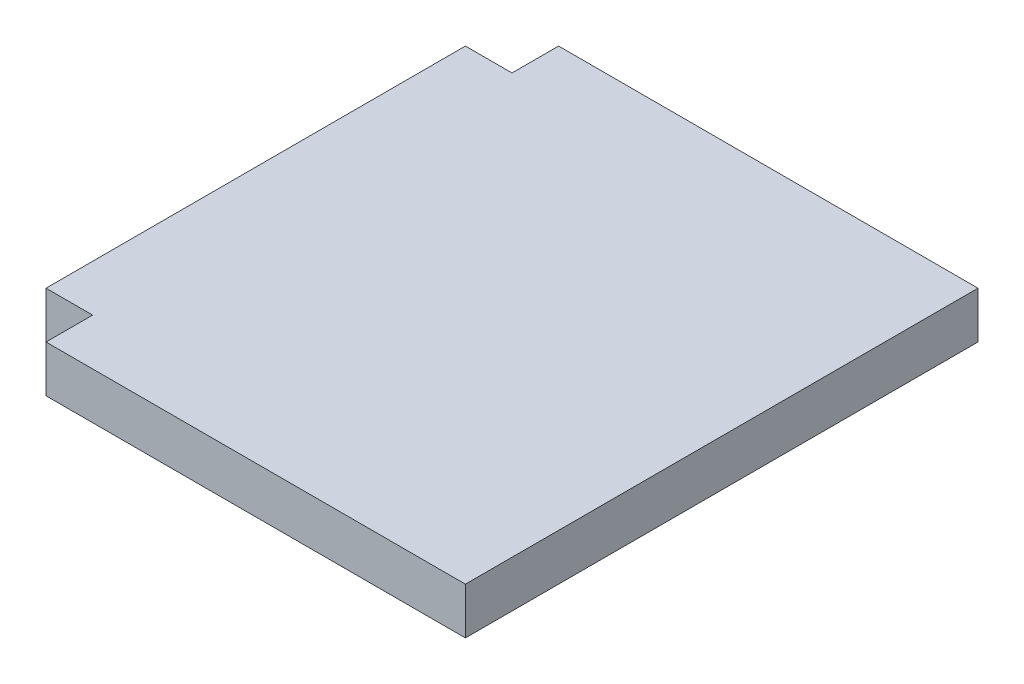
SolidWorks part; units mm, degrees
ref_plane "Alzado" through (0, 0, 0) normal (0, 0, 1) x (1, 0, 0)
ref_plane "Planta" through (0, 0, 0) normal (0, 1, 0) x (1, 0, 0)
ref_plane "Vista lateral" through (0, 0, 0) normal (1, 0, 0) x (0, 0, -1)
sketch "Croquis1" plane through (0, 0, 0) normal (0, 1, 0) x (1, 0, 0)
  line L1 (-250, 275) -> (250, 275)
  line L2 (-250, 275) -> (-250, -275)
  line L3 (-250, -275) -> (250, -275)
  line L4 (250, 275) -> (250, -275)
  line L5 (-250, 275) -> (250, -275) construction
  line L6 (-250, -275) -> (250, 275) construction
  point P0 (0, 0)
  point P7 (0, 0)
  dimension "D1" = 550
  dimension "D2" = 500
extrude "Saliente-Extruir1" add sketch "Croquis1" along normal blind 50
sketch "Croquis2" plane through (0, 50, 0) normal (0, 1, 0) x (1, 0, 0)
  line L0 (-250, 275) -> (-250, -275) construction
  line L1 (-250, 275) -> (-200, 275)
  line L2 (-250, 275) -> (-250, 225)
  line L3 (-250, 225) -> (-200, 225)
  line L4 (-200, 275) -> (-200, 225)
  line L5 (-250, 275) -> (-200, 225) construction
  line L6 (-250, 225) -> (-200, 275) construction
  line L7 (250, 275) -> (-250, 275) construction
  point P0 (-225, 250)
  dimension "D1" = 50
  dimension "D2" = 50
extrude "Cortar-Extruir1" cut sketch "Croquis2" against normal up to surface (50 mm away) up to face at (0, 0, 0)
pattern_linear "MatrizL1" count 2 spacing 500 along (0, 0, 1) of "Cortar-Extruir1"
